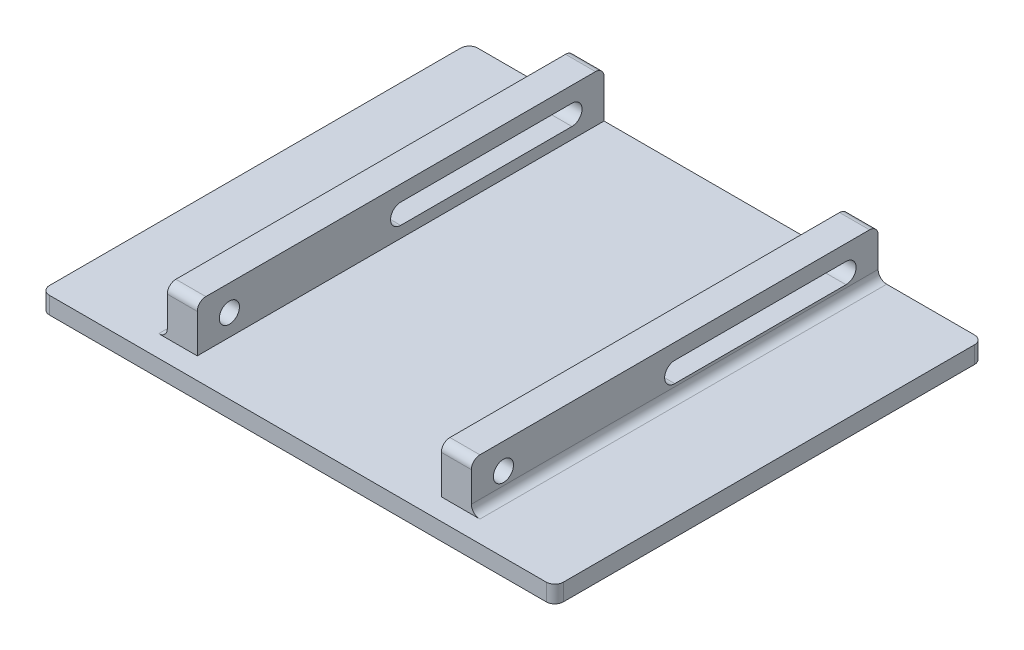
SolidWorks part; units mm, degrees
ref_plane "前视基准面" through (0, 0, 0) normal (0, 0, 1) x (1, 0, 0)
ref_plane "上视基准面" through (0, 0, 0) normal (0, 1, 0) x (1, 0, 0)
ref_plane "右视基准面" through (0, 0, 0) normal (1, 0, 0) x (0, 0, -1)
sketch "草图1" plane through (0, 0, 0) normal (0, 1, 0) x (1, 0, 0)
  line L1 (-60, 67.5) -> (60, 67.5)
  line L2 (-60, 67.5) -> (-60, -67.5)
  line L3 (-60, -67.5) -> (60, -67.5)
  line L4 (60, 67.5) -> (60, -67.5)
  line L5 (-60, 67.5) -> (60, -67.5) construction
  line L6 (-60, -67.5) -> (60, 67.5) construction
  point P0 (0, 0)
  dimension "D1" = 120
  dimension "D2" = 135
extrude "凸台-拉伸1" add sketch "草图1" along normal blind 4
sketch "草图2" plane through (0, 4, 0) normal (0, 1, 0) x (1, 0, 0)
  line L0 (0, 67.5) -> (0, -67.5) construction
  line L1 (60, 67.5) -> (-60, 67.5) construction
  line L2 (-60, -67.5) -> (60, -67.5) construction
  line L3 (-28.5, 67.5) -> (-35.5, 67.5)
  line L4 (-35.5, 67.5) -> (-35.5, -27.5)
  line L5 (-35.5, -27.5) -> (-28.5, -27.5)
  line L6 (-28.5, -27.5) -> (-28.5, 67.5)
  line L7 (35.5, -27.5) -> (28.5, -27.5)
  line L8 (28.5, -27.5) -> (28.5, 67.5)
  line L9 (35.5, 67.5) -> (35.5, -27.5)
  line L10 (28.5, 67.5) -> (35.5, 67.5)
  dimension "D1" = 28.5
  dimension "D2" = 7
  dimension "D3" = 95
extrude "凸台-拉伸2" add sketch "草图2" along normal blind 11
sketch "草图4" plane through (-35.5, 0, 0) normal (-1, 0, 0) x (0, 0, 1)
  line L0 (-73.9554, 9) -> (32.264, 9) construction
  line L1 (-67.5, 4) -> (67.5, 4) construction
  line L2 (27.5, 15) -> (27.5, 4) construction
  line L3 (-67.5, 15) -> (-67.5, 4) construction
  line L4 (-60, 11.35) -> (-20, 11.35)
  line L5 (-20, 6.65) -> (-60, 6.65)
  circle A0 centre (20, 9) radius 2.35
  arc A1 (-60, 11.35) -> (-60, 6.65) centre (-60, 9) ccw
  arc A2 (-20, 6.65) -> (-20, 11.35) centre (-20, 9) ccw
  dimension "D2" = 7.5
  dimension "D3" = 7.5
  dimension "D4" = 40
  dimension "D5" = 4.7
  dimension "D6" = 4.7
  dimension "D7" = 4.7
  dimension "D1" = 5
extrude "切除-拉伸2" cut sketch "草图4" against normal through all
sketch "草图5" plane through (0, 4, 0) normal (0, 1, 0) x (1, 0, 0)
  line L0 (-60, 67.5) -> (-60, -67.5) construction
  line L1 (60, -67.5) -> (-60, -67.5)
  line L2 (60, -67.5) -> (60, -32.5)
  line L3 (60, -32.5) -> (-60, -32.5)
  line L4 (-60, -67.5) -> (-60, -32.5)
  dimension "D1" = 35
extrude "切除-拉伸3" cut sketch "草图5" against normal blind 10
fillet "圆角1" radius 2 10 edges at (60, 2, -67.5) (-60, 2, -67.5) (-60, 2, 32.5) (60, 2, 32.5) (35.5, 4, -20) (-35.5, 4, -20) (32, 15, -67.5) (32, 15, 27.5) (-32, 15, 27.5) (-32, 15, -67.5)
